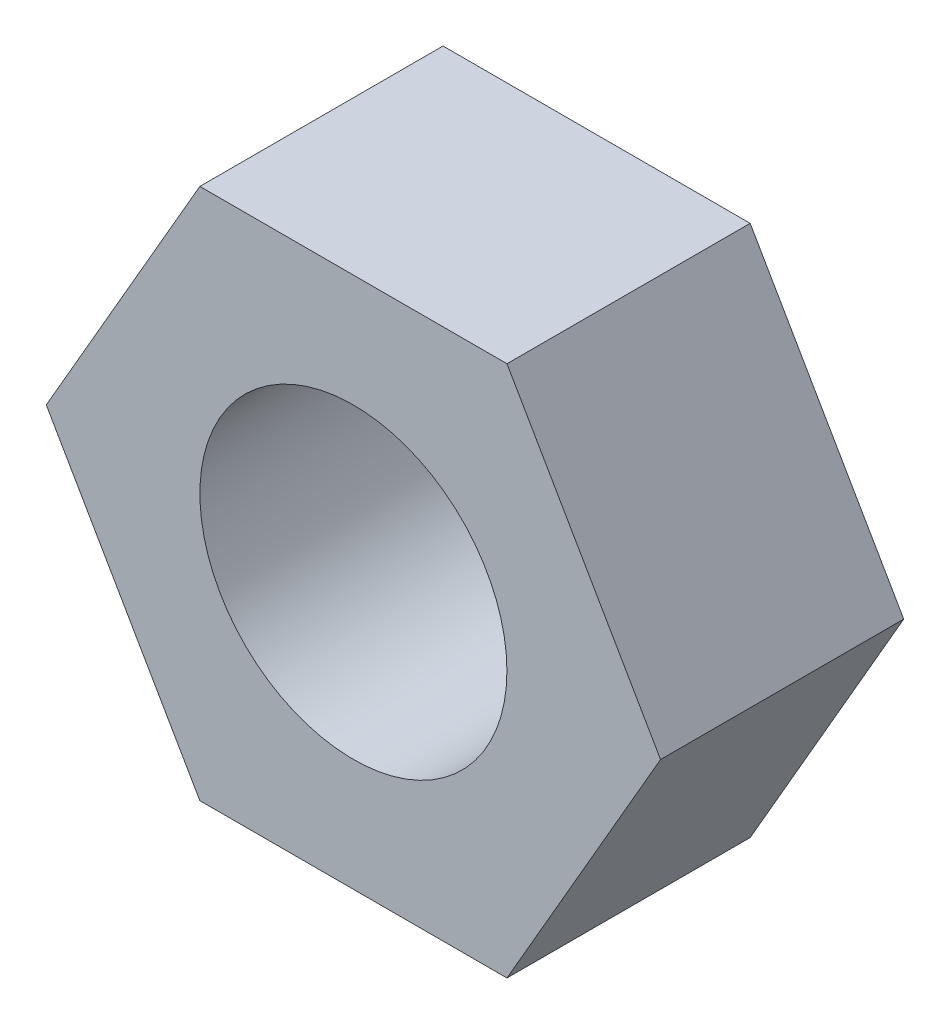
SolidWorks part; units mm, degrees
ref_plane "前视基准面" through (0, 0, 0) normal (0, 0, 1) x (1, 0, 0)
ref_plane "上视基准面" through (0, 0, 0) normal (0, 1, 0) x (1, 0, 0)
ref_plane "右视基准面" through (0, 0, 0) normal (1, 0, 0) x (0, 0, -1)
other "Configuration Table"
sketch "Sketch_Hex_blank" plane through (0, 0, 0) normal (0, 0, 1) x (1, 0, 0)
  line L0 (4.0415, 0) -> (2.0207, 3.5)
  line L1 (2.0207, 3.5) -> (-2.0207, 3.5)
  line L2 (-2.0207, 3.5) -> (-4.0415, 0)
  line L3 (-4.0415, 0) -> (-2.0207, -3.5)
  line L4 (-2.0207, -3.5) -> (2.0207, -3.5)
  line L5 (2.0207, -3.5) -> (4.0415, 0)
extrude "Hex_blank" add sketch "Sketch_Hex_blank" along normal blind 3.2 from offset 0
sketch "Sketch_Nominal_thread_envelope" plane through (0, 0, 0) normal (0, 0, 1) x (1, 0, 0)
  circle A0 centre (0, 0) radius 2.02
  dimension "D1" = 4.04
extrude "Nominal_thread_envelope" cut sketch "Sketch_Nominal_thread_envelope" along normal blind 5.2 from offset 1
